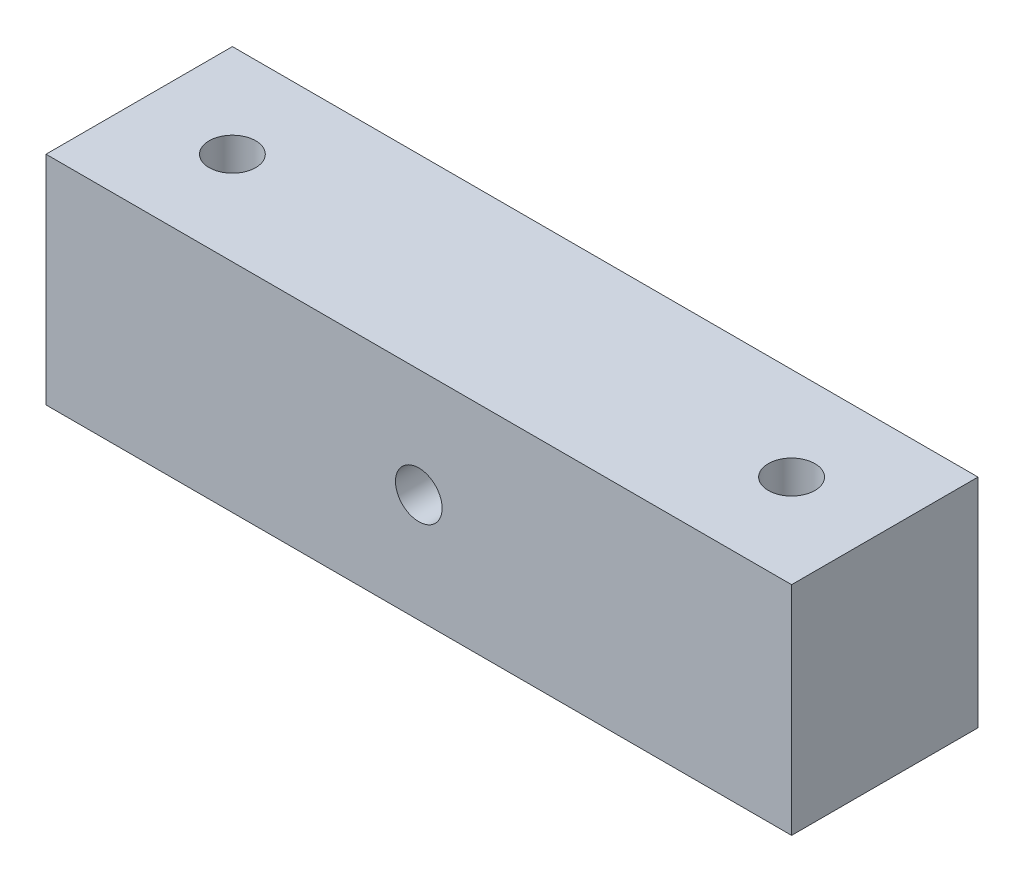
SolidWorks part; units mm, degrees
material "Copper"
ref_plane "Front Plane" through (0, 0, 0) normal (0, 0, 1) x (1, 0, 0)
ref_plane "Top Plane" through (0, 0, 0) normal (0, 1, 0) x (1, 0, 0)
ref_plane "Right Plane" through (0, 0, 0) normal (1, 0, 0) x (0, 0, -1)
sketch "Sketch1" plane through (0, 0, 0) normal (0, 1, 0) x (1, 0, 0)
  line L0 (0, 5) -> (40, 5) construction
  line L1 (0, 0) -> (40, 0)
  line L2 (0, 0) -> (0, 10)
  line L3 (0, 10) -> (40, 10)
  line L4 (40, 0) -> (40, 10)
  line L5 (5, 5) -> (5, 10) construction
  line L6 (35, 10) -> (35, 5) construction
  dimension "D1" = 5
  dimension "D2" = 5
  dimension "D3" = 5
  dimension "D4" = 5
  dimension "D5" = 40
extrude "Boss-Extrude1" add sketch "Sketch1" along normal blind 11.65
sketch "Sketch2" plane through (0, 11.65, 0) normal (0, 1, 0) x (1, 0, 0)
  point P0 (35, 5)
  point P2 (5, 5)
hole_wizard "M3x0.5 Tapped Hole3" positions "3DSketch1" profile "Sketch3" tap size "M3x0.5" standard "ANSI Metric" end condition through all
sketch3d "3DSketch1"
  point P0 (5, 11.65, -5)
  point P3 (35, 11.65, -5)
sketch "Sketch3" plane through (5, 11.65, -5) normal (1, 0, 0) x (0, 0, 1)
  line L0 (0, 0) -> (0, 11.65)
  line L1 (0, 11.65) -> (1.25, 11.65)
  line L2 (1.25, 11.65) -> (1.25, 0)
  line L5 (1.25, 0) -> (0, 0)
  line L11 (0, -6.35) -> (0, 107.95) construction
  dimension "Thru Tap Drill Dia." = 2.5
  dimension "Thru Tap Drill Depth" = 11.65
cosmetic thread "Hole Thread1" parameters "D2"=3
cosmetic thread "Hole Thread2" parameters "D2"=3
sketch "Sketch4" plane through (0, 0, -10) normal (0, 0, -1) x (-1, 0, 0)
  line L0 (-40, 5.825) -> (0, 5.825)
  line L1 (-40, 11.65) -> (-40, 0) construction
  line L2 (0, 11.65) -> (0, 0) construction
hole_wizard "M3x0.5 Tapped Hole4" positions "3DSketch2" profile "Sketch5" tap size "M3x0.5" standard "ANSI Metric" end condition through all
sketch3d "3DSketch2"
  line L0 (40, 5.825, -10) -> (0, 5.825, -10) construction
  point P0 (20, 5.825, -10)
cosmetic thread "Hole Thread3" parameters "D2"=3
sketch "Sketch5" plane through (20, 5.825, -10) normal (1, 0, 0) x (0, 1, 0)
  line L0 (0, 0) -> (0, 10)
  line L1 (0, 10) -> (1.25, 10)
  line L2 (1.25, 10) -> (1.25, 0)
  line L5 (1.25, 0) -> (0, 0)
  line L11 (0, -6.35) -> (0, 107.95) construction
  dimension "Thru Tap Drill Dia." = 2.5
  dimension "Thru Tap Drill Depth" = 10
equation "\"D2@Sketch1\"=\"D1@Sketch1\""
equation "\"D3@Sketch1\"=\"D1@Sketch1\""
